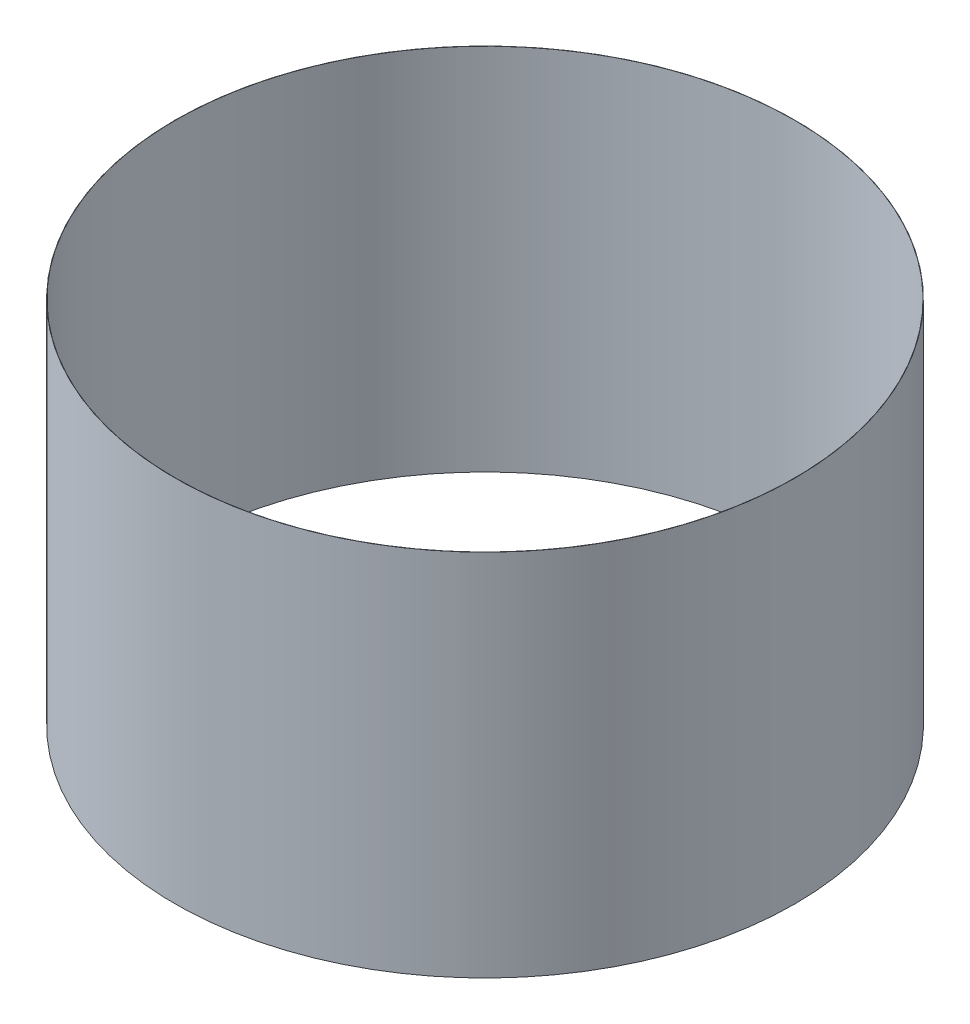
SolidWorks part; units mm, degrees
ref_plane "Front Plane" through (0, 0, 0) normal (0, 0, 1) x (1, 0, 0)
ref_plane "Top Plane" through (0, 0, 0) normal (0, 1, 0) x (1, 0, 0)
ref_plane "Right Plane" through (0, 0, 0) normal (1, 0, 0) x (0, 0, -1)
sketch "Sketch1" plane through (0, 0, 0) normal (0, 1, 0) x (1, 0, 0)
  circle A0 centre (0, 0) radius 126
  dimension "D1" = 252
extrude "Extrude-Thin1" add sketch "Sketch1" along normal blind 150 thin contours A0
